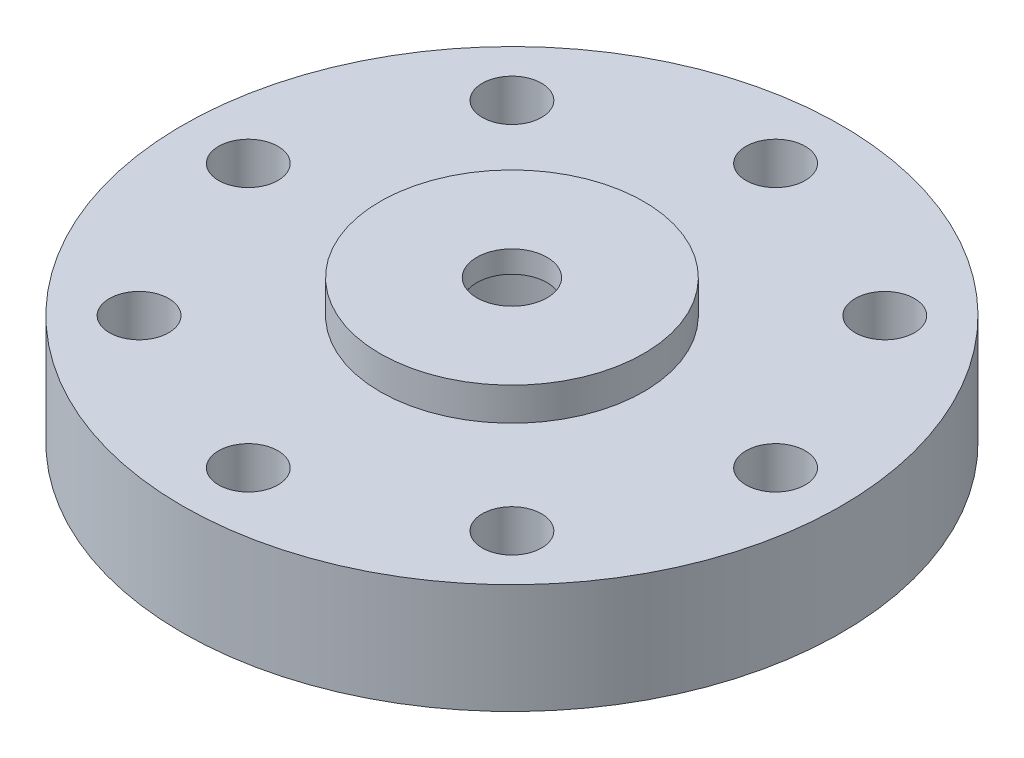
SolidWorks part; units mm, degrees
ref_plane "Plan de face" through (0, 0, 0) normal (0, 0, 1) x (1, 0, 0)
ref_plane "Plan de dessus" through (0, 0, 0) normal (0, 1, 0) x (1, 0, 0)
ref_plane "Plan de droite" through (0, 0, 0) normal (1, 0, 0) x (0, 0, -1)
sketch "Esquisse1" plane through (0, 0, 0) normal (0, 1, 0) x (1, 0, 0)
  circle A0 centre (0, 0) radius 15
  dimension "D1" = 30
extrude "Boss.-Extru.1" add sketch "Esquisse1" along normal blind 5
sketch "Esquisse2" plane through (0, 5, 0) normal (0, 1, 0) x (1, 0, 0)
  circle A0 centre (0, 0) radius 6
  dimension "D1" = 12
extrude "Boss.-Extru.2" add sketch "Esquisse2" along normal blind 1.5
sketch "Esquisse3" plane through (0, 0, 0) normal (0, -1, 0) x (1, 0, 0)
  circle A0 centre (0, 0) radius 1.6
  dimension "D1" = 3.2
extrude "Enlèv. mat.-Extru.1" cut sketch "Esquisse3" against normal through all
sketch "Esquisse4" plane through (0, 0, 0) normal (0, -1, 0) x (1, 0, 0)
  circle A0 centre (0, 0) radius 3.7
  dimension "D1" = 7.4
extrude "Enlèv. mat.-Extru.2" cut sketch "Esquisse4" against normal blind 5.5
hole_wizard "Dégagement M2.51" positions "Esquisse5" profile "Esquisse7" hole size "M2.5" standard "ISO" end condition through all
sketch "Esquisse5" plane through (0, 5, 0) normal (0, 1, 0) x (1, 0, 0)
  circle A0 centre (0, 0) radius 12 construction
  point P9 (-12, 0)
  point P14 (-8.4853, 8.4853)
  point P15 (0, 12)
  point P16 (8.4853, 8.4853)
  point P17 (12, 0)
  point P18 (8.4853, -8.4853)
  point P19 (0, -12)
  point P20 (-8.4853, -8.4853)
  point P21 (0, 0)
  dimension "D1" = 24
  dimension "D2" = 8
sketch "Esquisse7" plane through (0, 5, 0) normal (1, 0, 0) x (0, 0, 1)
  line L0 (0, 0) -> (0, 5)
  line L1 (0, 5) -> (1.35, 5)
  line L2 (1.35, 5) -> (1.35, 0)
  line L5 (1.35, 0) -> (0, 0)
  line L11 (0, -6.35) -> (0, 107.95) construction
  dimension "Diamètre du perçage jusqu'au prochain" = 2.7
  dimension "Profondeur du perçage jusqu'au prochain" = 5
